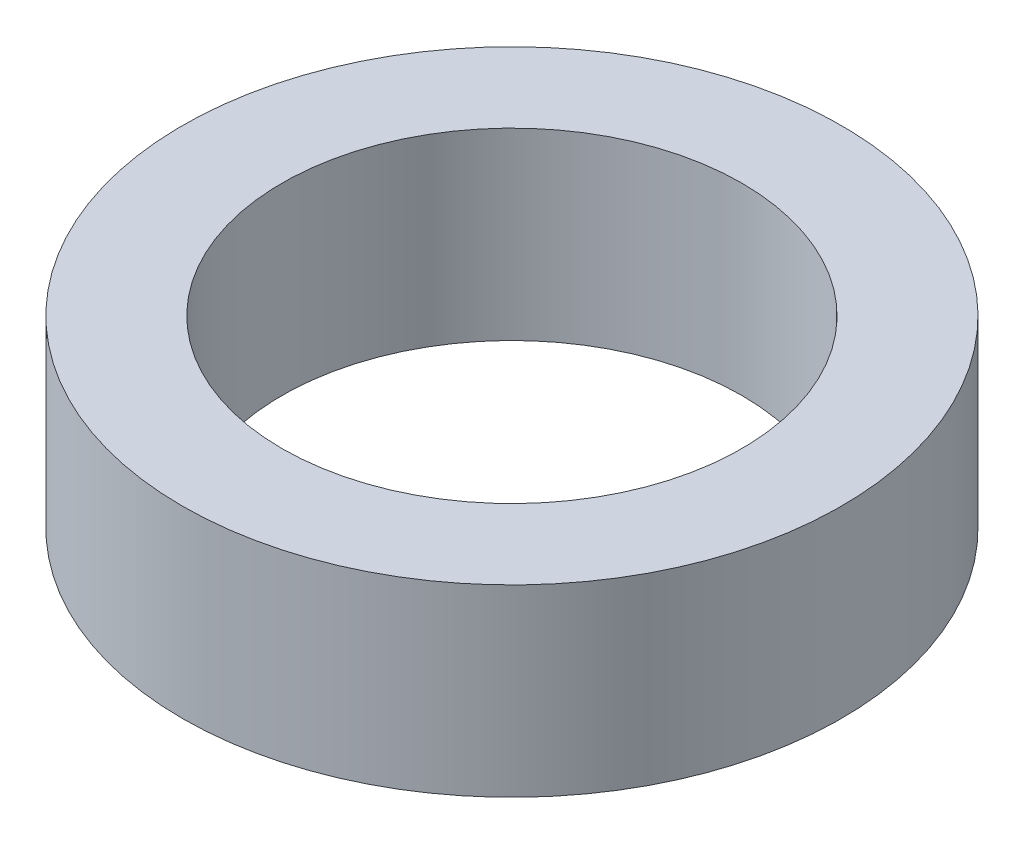
SolidWorks part; units mm, degrees
ref_plane "前视基准面" through (0, 0, 0) normal (0, 0, 1) x (1, 0, 0)
ref_plane "上视基准面" through (0, 0, 0) normal (0, 1, 0) x (1, 0, 0)
ref_plane "右视基准面" through (0, 0, 0) normal (1, 0, 0) x (0, 0, -1)
sketch "草图1" plane through (0, 0, 0) normal (0, 1, 0) x (1, 0, 0)
  circle A0 centre (0, 0) radius 15
  circle A1 centre (0, 0) radius 21.5
  dimension "D1" = 43
  dimension "D2" = 30
extrude "凸台-拉伸1" add sketch "草图1" along normal blind 12
